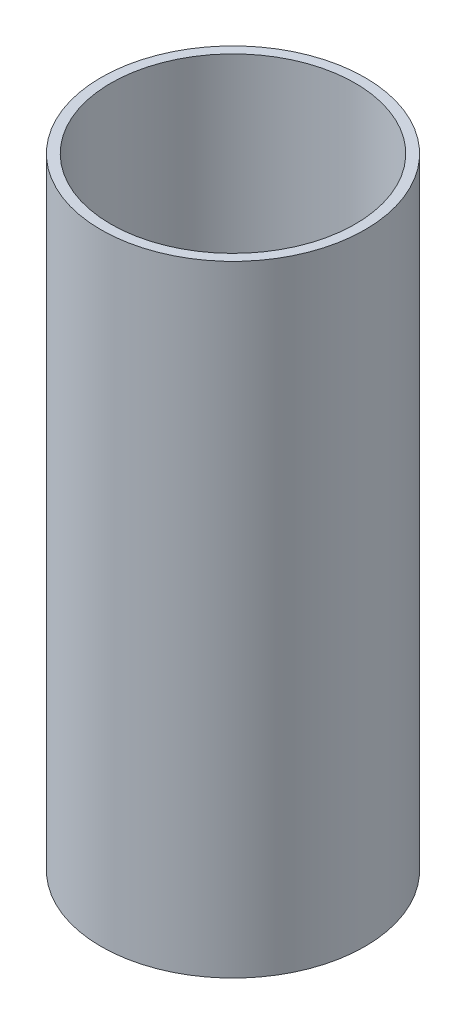
SolidWorks part; units mm, degrees
ref_plane "Front Plane" through (0, 0, 0) normal (0, 0, 1) x (1, 0, 0)
ref_plane "Top Plane" through (0, 0, 0) normal (0, 1, 0) x (1, 0, 0)
ref_plane "Right Plane" through (0, 0, 0) normal (1, 0, 0) x (0, 0, -1)
sketch "Sketch2" plane through (0, 0, 0) normal (0, 1, 0) x (1, 0, 0)
  circle A0 centre (0, 0) radius 54
  circle A1 centre (0, 0) radius 50
extrude "Boss-Extrude1" add sketch "Sketch2" along normal blind 254
